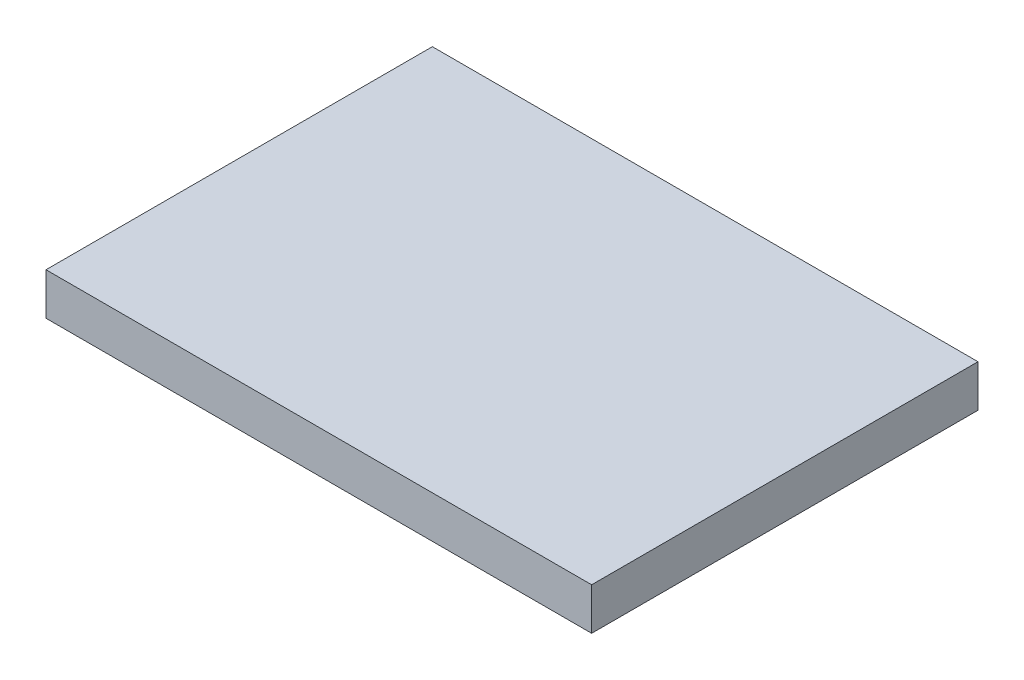
SolidWorks part; units mm, degrees
ref_plane "Front Plane" through (0, 0, 0) normal (0, 0, 1) x (1, 0, 0)
ref_plane "Top Plane" through (0, 0, 0) normal (0, 1, 0) x (1, 0, 0)
ref_plane "Right Plane" through (0, 0, 0) normal (1, 0, 0) x (0, 0, -1)
sketch "Sketch1" plane through (0, 0, 0) normal (0, 1, 0) x (1, 0, 0)
  line L1 (0, 0) -> (116.8, 0)
  line L2 (0, 0) -> (0, 82.7)
  line L3 (0, 82.7) -> (116.8, 82.7)
  line L4 (116.8, 0) -> (116.8, 82.7)
  dimension "D1" = 116.8
  dimension "D2" = 82.7
extrude "Boss-Extrude1" add sketch "Sketch1" along normal blind 9
